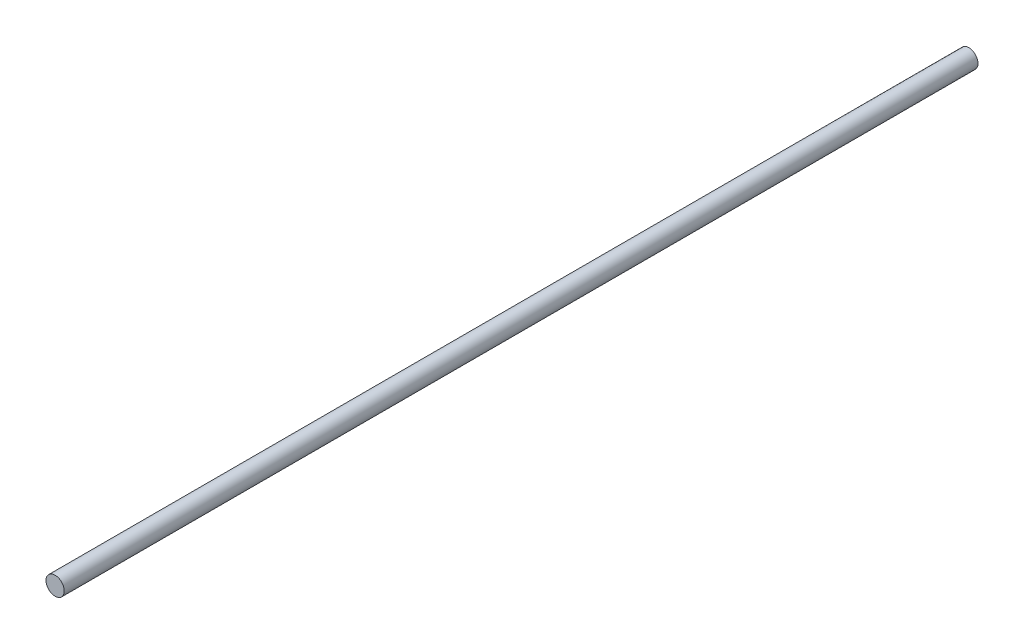
SolidWorks part; units mm, degrees
ref_plane "Спереди" through (0, 0, 0) normal (0, 0, 1) x (1, 0, 0)
ref_plane "Сверху" through (0, 0, 0) normal (0, 1, 0) x (1, 0, 0)
ref_plane "Справа" through (0, 0, 0) normal (1, 0, 0) x (0, 0, -1)
sketch "Эскиз1" plane through (0, 0, 0) normal (0, 0, 1) x (1, 0, 0)
  circle A0 centre (0, 0) radius 4
  dimension "D1" = 8
extrude "Бобышка-Вытянуть1" add sketch "Эскиз1" along normal blind 400
cosmetic thread "Условное изображение резьбы1" parameters "D2"=6.891
